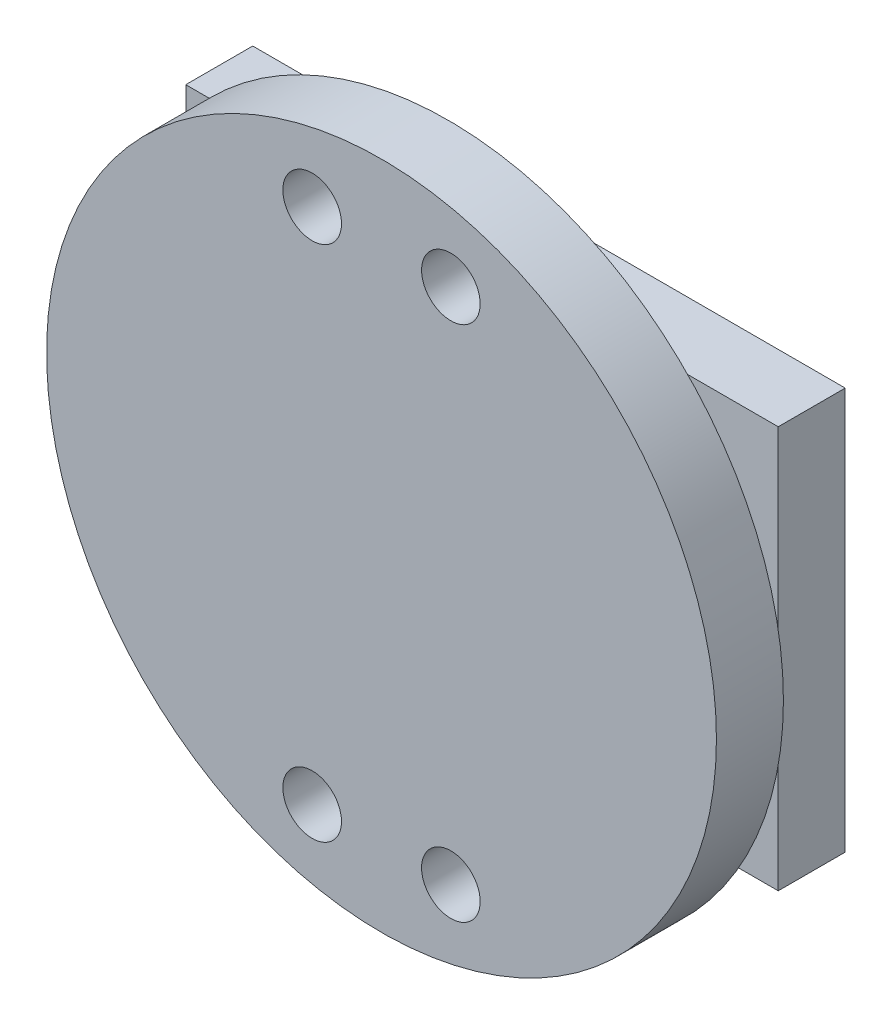
SolidWorks part; units mm, degrees
ref_plane "前视基准面" through (0, 0, 0) normal (0, 0, 1) x (1, 0, 0)
ref_plane "上视基准面" through (0, 0, 0) normal (0, 1, 0) x (1, 0, 0)
ref_plane "右视基准面" through (0, 0, 0) normal (1, 0, 0) x (0, 0, -1)
other "Configuration Table"
sketch "草图1" plane through (0, 0, 0) normal (0, 0, 1) x (1, 0, 0)
  line L1 (0, 0) -> (35.38, 0)
  line L2 (0, 0) -> (0, -24)
  line L3 (0, -24) -> (35.38, -24)
  line L4 (35.38, 0) -> (35.38, -24)
  point P4 (0, 0)
  dimension "D1" = 24
  dimension "D2" = 35.38
extrude "凸台-拉伸1" add sketch "草图1" along normal blind 4
sketch "草图2" plane through (0, 0, 4) normal (0, 0, 1) x (1, 0, 0)
  line L0 (-5.5417, -12) -> (40.9217, -12) construction
  line L1 (17.69, 11.3191) -> (17.69, -34.1546) construction
  line L2 (0, -24) -> (35.38, -24) construction
  line L3 (35.38, 0) -> (0, 0) construction
  line L4 (35.38, -24) -> (35.38, 0) construction
  line L5 (0, 0) -> (0, -24) construction
  circle A0 centre (17.69, -12) radius 10
  point P14 (23.2214, -12)
  point P15 (0, 0)
  dimension "D1" = 20
extrude "凸台-拉伸2" add sketch "草图2" along normal blind 2
sketch "草图3" plane through (0, 0, 6) normal (0, 0, 1) x (1, 0, 0)
  circle A0 centre (17.69, -12) radius 20
  dimension "D1" = 40
extrude "凸台-拉伸3" add sketch "草图3" along normal blind 4
sketch "草图4" plane through (0, 0, 6) normal (0, 0, -1) x (-1, 0, 0)
  line L0 (-17.69, -12) -> (-17.69, 9.4828) construction
  line L1 (-17.69, -12) -> (8.1588, -12) construction
  line L2 (-17.69, -12) -> (-13.5489, 3.4548) construction
  circle A0 centre (-13.5489, 3.4548) radius 1.75
  circle A1 centre (-21.8311, 3.4548) radius 1.75
  circle A2 centre (-13.5489, -27.4548) radius 1.75
  circle A3 centre (-21.8311, -27.4548) radius 1.75
  dimension "D3" = 3.5
  dimension "D1" = 15
  dimension "D2" = 16
extrude "切除-拉伸1" cut sketch "草图4" against normal blind 10
